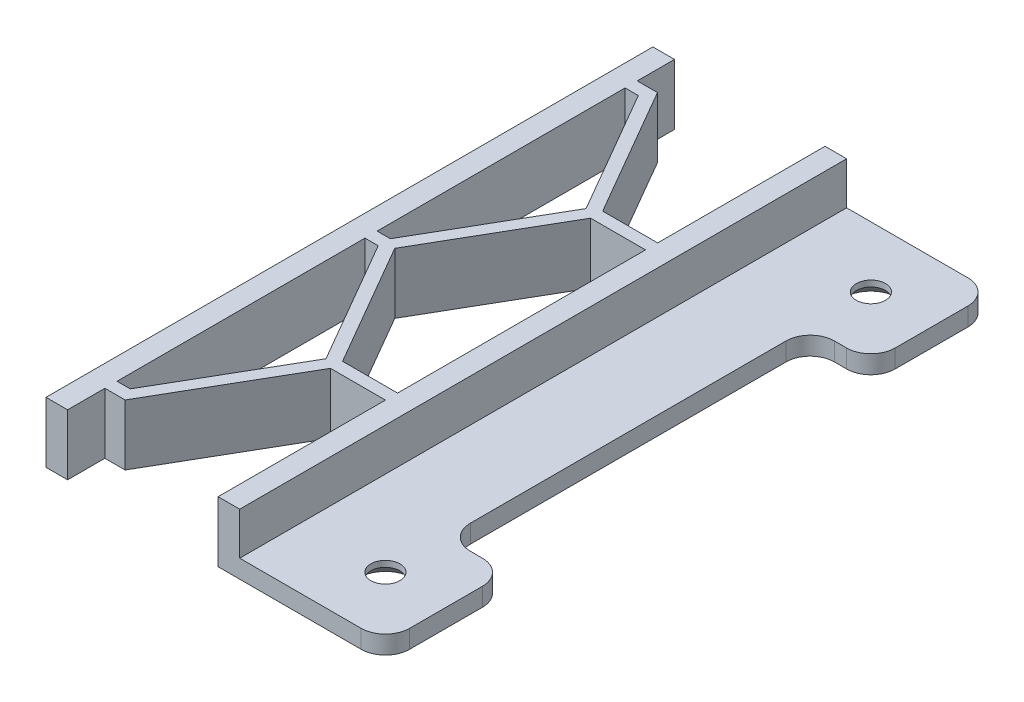
SolidWorks part; units mm, degrees
ref_plane "Front Plane" through (0, 0, 0) normal (0, 0, 1) x (1, 0, 0)
ref_plane "Top Plane" through (0, 0, 0) normal (0, 1, 0) x (1, 0, 0)
ref_plane "Right Plane" through (0, 0, 0) normal (1, 0, 0) x (0, 0, -1)
sketch "Sketch1" plane through (0, 0, 0) normal (0, 1, 0) x (1, 0, 0)
  line L0 (-14.18, 50) -> (-14.18, 46.9286)
  line L1 (-15.96, 50) -> (-14.18, 50)
  line L2 (-15.96, 50) -> (-15.96, 0)
  line L3 (-15.96, 0) -> (-14.18, 0)
  line L5 (-1.78, 50) -> (0, 50)
  line L7 (-1.78, 0) -> (0, 0)
  line L8 (0, 50) -> (0, 0)
  line L9 (-1.78, 50) -> (-1.78, 36.2143)
  line L18 (-14.18, 25) -> (-1.78, 25) construction
  line L20 (-14.18, 25) -> (-12.8022, 25) construction
  line L21 (-12.8022, 25) -> (-6.6022, 35.7143) construction
  line L22 (-6.6022, 35.7143) -> (-1.78, 35.7143) construction
  line L23 (-6.6022, 35.7143) -> (-12.8022, 46.4286) construction
  line L24 (-12.8022, 46.4286) -> (-14.18, 46.4286) construction
  line L25 (-12.8022, 3.5714) -> (-14.18, 3.5714) construction
  line L26 (-6.6022, 14.2857) -> (-12.8022, 3.5714) construction
  line L27 (-6.6022, 14.2857) -> (-1.78, 14.2857) construction
  line L28 (-12.8022, 25) -> (-6.6022, 14.2857) construction
  line L29 (-7.1799, 35.7143) -> (-13.0906, 45.9286)
  line L30 (-13.0906, 45.9286) -> (-14.18, 45.9286)
  line L31 (-6.3139, 36.2143) -> (-1.78, 36.2143)
  line L32 (-13.0906, 25.5) -> (-7.1799, 35.7143)
  line L33 (-14.18, 25.5) -> (-13.0906, 25.5)
  line L34 (-12.2245, 25) -> (-6.3139, 14.7857)
  line L35 (-6.3139, 14.7857) -> (-1.78, 14.7857)
  line L36 (-6.3139, 13.7857) -> (-12.5139, 3.0714)
  line L37 (-12.5139, 3.0714) -> (-14.18, 3.0714)
  line L38 (-6.3139, 36.2143) -> (-12.5139, 46.9286)
  line L39 (-12.5139, 46.9286) -> (-14.18, 46.9286)
  line L40 (-6.3139, 35.2143) -> (-1.78, 35.2143)
  line L41 (-12.3695, 24.7496) -> (-6.3139, 35.2143)
  line L42 (-14.18, 24.5) -> (-13.0906, 24.5)
  line L43 (-13.0906, 24.5) -> (-7.1799, 14.2857)
  line L44 (-6.3139, 13.7857) -> (-1.78, 13.7857)
  line L45 (-7.1799, 14.2857) -> (-13.0906, 4.0714)
  line L46 (-13.0906, 4.0714) -> (-14.18, 4.0714)
  line L47 (-14.18, 45.9286) -> (-14.18, 25.5)
  line L48 (-14.18, 24.5) -> (-14.18, 4.0714)
  line L49 (-14.18, 3.0714) -> (-14.18, 0)
  line L50 (-1.78, 35.2143) -> (-1.78, 14.7857)
  line L51 (-1.78, 13.7857) -> (-1.78, 0)
  line L52 (-13.0906, 25.5) -> (-12.8022, 25.5) construction
  line L53 (-6.6022, 36.2143) -> (-6.3139, 36.2143) construction
  line L54 (-6.6022, 36.2143) -> (-1.78, 36.2143) construction
  line L55 (-6.1695, 35.9647) -> (-6.3139, 36.2143) construction
  line L56 (-6.1695, 35.9647) -> (-12.5139, 46.9286) construction
  line L57 (-6.3139, 35.2143) -> (-6.1695, 35.4639) construction
  line L58 (-12.3695, 24.7496) -> (-6.1695, 35.4639) construction
  line L59 (-6.6022, 35.2143) -> (-6.3139, 35.2143) construction
  line L60 (-6.6022, 35.2143) -> (-1.78, 35.2143) construction
  line L61 (-7.035, 35.4639) -> (-7.1799, 35.7143) construction
  line L62 (-7.035, 35.4639) -> (-13.0906, 45.9286) construction
  line L63 (-7.1799, 35.7143) -> (-7.035, 35.9647) construction
  line L64 (-13.235, 25.2504) -> (-7.035, 35.9647) construction
  line L65 (-12.3695, 25.2504) -> (-12.2245, 25) construction
  line L66 (-12.3695, 25.2504) -> (-6.1695, 14.5361) construction
  line L67 (-14.18, 25.5) -> (-12.8022, 25.5) construction
  line L68 (-13.235, 25.2504) -> (-13.0906, 25.5) construction
  line L69 (-13.235, 24.7496) -> (-13.0906, 24.5) construction
  line L70 (-13.235, 24.7496) -> (-7.035, 14.0353) construction
  line L71 (-13.0906, 24.5) -> (-12.8022, 24.5) construction
  line L72 (-14.18, 24.5) -> (-12.8022, 24.5) construction
  line L73 (-6.6022, 14.7857) -> (-6.3139, 14.7857) construction
  line L74 (-6.6022, 14.7857) -> (-1.78, 14.7857) construction
  line L75 (-6.3139, 14.7857) -> (-6.1695, 14.5361) construction
  line L76 (-6.1695, 14.0353) -> (-6.3139, 13.7857) construction
  line L77 (-6.1695, 14.0353) -> (-12.5139, 3.0714) construction
  line L78 (-6.6022, 13.7857) -> (-6.3139, 13.7857) construction
  line L79 (-6.6022, 13.7857) -> (-1.78, 13.7857) construction
  line L80 (-7.1799, 14.2857) -> (-7.035, 14.0353) construction
  line L81 (-7.035, 14.5361) -> (-7.1799, 14.2857) construction
  line L82 (-7.035, 14.5361) -> (-13.0906, 4.0714) construction
  dimension "D2" = 12.4
  dimension "D4" = 1.3778
  dimension "D5" = 6.2
  dimension "D7" = 14.2857
  dimension "D1" = 50
  dimension "D3" = 1.78
  dimension "D10" = 25
  dimension "D11" = 25
  dimension "D6" = 1.78
  dimension "D8" = 0.5
  dimension "D9" = 0.5
extrude "Boss-Extrude1" add sketch "Sketch1" along normal blind 5
sketch "Sketch5" plane through (0, 0, 0) normal (0, -1, 0) x (1, 0, 0)
  line L0 (12, -40) -> (12, -50)
  line L1 (0, 0) -> (12, 0)
  line L2 (0, 0) -> (0, -50)
  line L3 (0, -50) -> (12, -50)
  line L4 (12, 0) -> (12, -10)
  line L5 (12, -10) -> (7, -10)
  line L7 (12, -40) -> (7, -40)
  line L8 (7, -10) -> (7, -40)
  circle A0 centre (7, -5) radius 1.1 construction
  circle A1 centre (7, -45) radius 1.1 construction
  point P9 (7, -25)
  point P10 (0, -25)
  point P17 (12, -5)
  point P19 (12, -45)
  dimension "D4" = 2.2
  dimension "D1" = 30
  dimension "D2" = 12
  dimension "D3" = 5
extrude "Boss-Extrude3" add sketch "Sketch5" against normal blind 1.5
fillet "Fillet1" radius 2 6 edges at (12, 0.75, -10) (7, 0.75, -10) (7, 0.75, -40) (12, 0.75, -40) (12, 0.75, -50) (12, 0.75, 0)
hole_wizard "CSK for M2 Flat Head Machine Screw1" positions "3DSketch1" profile "Sketch6" countersink size "M2" standard "ANSI Metric" end condition up to next
sketch3d "3DSketch1"
  point P0 (7, 0, -5)
  point P3 (7, 0, -45)
sketch "Sketch6" plane through (7, 0, -5) normal (1, 0, 0) x (0, 0, -1)
  line L0 (0, 0) -> (0, 1.5)
  line L1 (0, 1.5) -> (1.2, 1.5)
  line L2 (1.2, 1.5) -> (1.2, 1)
  line L3 (1.2, 1) -> (2.2, 0)
  line L5 (2.2, 0) -> (0, 0)
  line L6 (-1.2, 1) -> (-2.2, 0) construction
  line L11 (0, -6.35) -> (0, 107.95) construction
  dimension "Thru Hole Dia." = 2.4
  dimension "Thru Hole Depth" = 1.5
  dimension "Near C'Sink Dia." = 4.4
  dimension "Near C'Sink Angle" = 90
chamfer "Chamfer1" [suppressed] distance 2 angle 45
equation "\"bracket-length\"= 50"
equation "\"gap\"= 15 - 2.6"
equation "\"D4@Sketch1\"=\"gap\"/9"
equation "\"D5@Sketch1\"=\"gap\"/2"
equation "\"D2@Sketch1\"=\"gap\""
equation "\"D7@Sketch1\"=\"bracket-length\"/3.5"
equation "\"D1@Sketch1\"=\"bracket-length\""
equation "\"D10@Sketch1\"=\"bracket-length\"/2"
